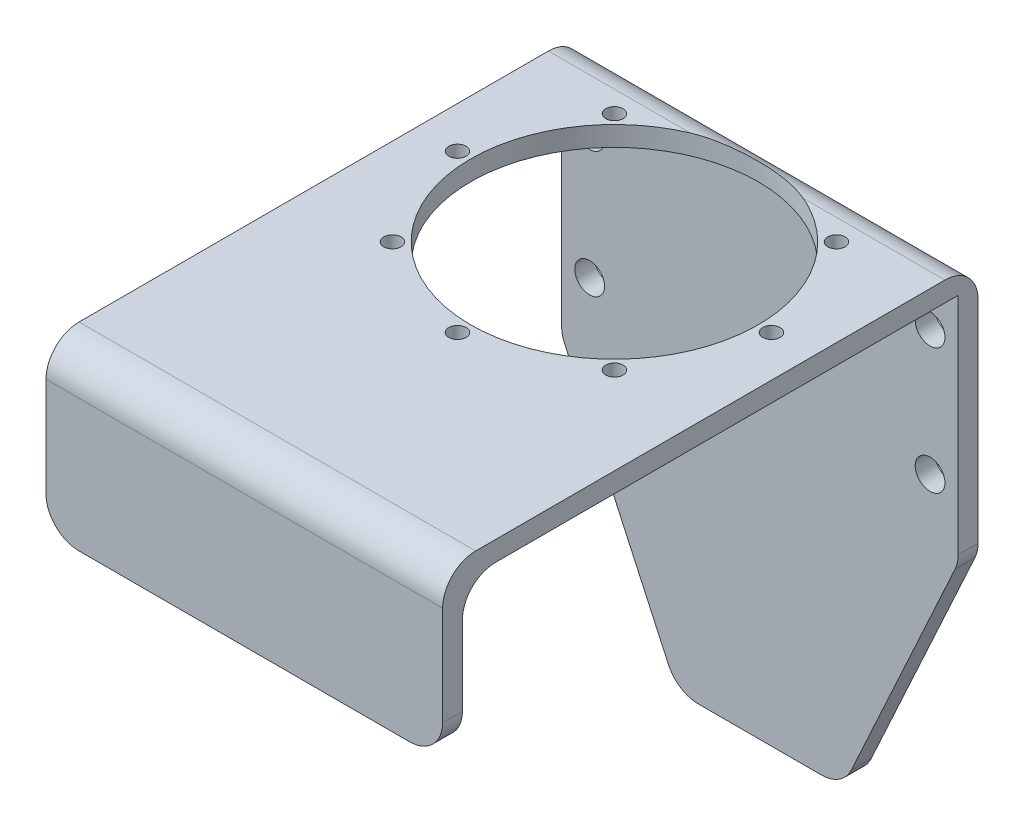
SolidWorks part; units mm, degrees
ref_plane "Alzado" through (0, 0, 0) normal (0, 0, 1) x (1, 0, 0)
ref_plane "Planta" through (0, 0, 0) normal (0, 1, 0) x (1, 0, 0)
ref_plane "Vista lateral" through (0, 0, 0) normal (1, 0, 0) x (0, 0, -1)
sketch "Croquis1" plane through (0, 0, 0) normal (0, 0, 1) x (1, 0, 0)
  line L7 (-92.102, -168.3) -> (-57.102, -244.5)
  line L8 (-92.102, -92.1) -> (27.898, -92.1) construction
  line L9 (-92.102, -92.1) -> (-92.102, -244.5) construction
  line L10 (-92.102, -244.5) -> (27.898, -244.5) construction
  line L11 (27.898, -92.1) -> (27.898, -244.5) construction
  line L12 (27.898, -92.1) -> (27.898, -244.5) construction
  line L13 (-92.102, -92.1) -> (27.898, -92.1) construction
  line L14 (-92.102, -92.1) -> (27.898, -92.1)
  line L15 (-92.102, -92.1) -> (-92.102, -168.3)
  line L17 (27.898, -92.1) -> (27.898, -168.3)
  line L22 (-57.102, -244.5) -> (-7.102, -244.5)
  line L23 (-7.102, -244.5) -> (27.898, -168.3)
  line L24 (-32.102, -168.3) -> (-32.102, -92.1) construction
  line L25 (-92.102, -168.3) -> (27.898, -168.3) construction
  line L26 (-32.102, -130.2) -> (-92.102, -130.2) construction
  line L27 (-62.102, -130.2) -> (-62.102, -92.1) construction
  circle A0 centre (-83.602, -111.15) radius 4.5
  circle A1 centre (-83.602, -149.25) radius 4.5
  circle A2 centre (19.398, -149.25) radius 4.5
  circle A3 centre (19.398, -111.15) radius 4.5
  point P5 (-32.102, -244.5)
  point P16 (-32.102, -244.5)
  point P21 (27.898, -168.3)
  point P24 (-62.102, -111.15)
  point P32 (-88.102, -111.15)
  dimension "D3" = 9
  dimension "D1" = 120
  dimension "D2" = 50
  dimension "D4" = 4
extrude "Saliente-Extruir1" add sketch "Croquis1" along normal blind 6
sketch "Croquis2" plane through (0, 0, 6) normal (0, 0, 1) x (1, 0, 0)
  line L0 (27.898, -168.3) -> (27.898, -92.1) construction
  line L6 (-92.102, -98.1) -> (27.898, -98.1)
  line L7 (-92.102, -98.1) -> (-92.102, -92.1)
  line L8 (-92.102, -92.1) -> (27.898, -92.1)
  line L9 (27.898, -98.1) -> (27.898, -92.1)
  dimension "D1" = 6
extrude "Saliente-Extruir2" add sketch "Croquis2" along normal up to surface (156 mm away)
sketch "Croquis3" plane through (0, 0, 162) normal (0, 0, 1) x (1, 0, 0)
  line L5 (-92.102, -98.1) -> (27.898, -98.1)
  line L6 (-92.102, -98.1) -> (-92.102, -142.1)
  line L7 (-92.102, -142.1) -> (27.898, -142.1)
  line L16 (27.898, -98.1) -> (27.898, -142.1)
  line L17 (27.898, -92.1) -> (-92.102, -92.1) construction
  line L18 (27.898, -168.3) -> (27.898, -98.1) construction
  dimension "50" = 50
extrude "Saliente-Extruir3" add sketch "Croquis3" against normal blind 6
fillet "Redondeo1" radius 10 9 edges at (-32.102, -98.1, 156) (-32.102, -92.1, 0) (-32.102, -92.1, 162) (-92.102, -142.1, 159) (27.898, -142.1, 159) (-92.102, -168.3, 3) (27.898, -168.3, 3) (-7.102, -244.5, 3) (-57.102, -244.5, 3)
sketch "Croquis4" plane through (0, -98.1, 0) normal (0, -1, 0) x (1, 0, 0)
  circle A2 centre (-65.6896, 16.4124) radius 2.621
  circle A3 centre (1.4855, 83.5876) radius 2.621
  circle A4 centre (1.4855, 83.5876) radius 2.621
  circle A5 centre (-65.6896, 16.4124) radius 2.621
  circle A6 centre (15.398, 50) radius 2.621
  circle A7 centre (15.398, 50) radius 2.621
  circle A9 centre (1.4855, 16.4124) radius 2.621
  circle A10 centre (1.4855, 16.4124) radius 2.621
  circle A12 centre (-65.6896, 83.5876) radius 2.621
  circle A13 centre (-65.6896, 83.5876) radius 2.621
  circle A15 centre (-79.602, 50) radius 2.621
  circle A16 centre (-32.102, 97.5) radius 2.621
  circle A17 centre (-32.102, 97.5) radius 2.621
  circle A18 centre (-79.602, 50) radius 2.621
  spline S0 degree 3 poles (-36.0819, 6.6207) (-32.1019, 6.4397) (-28.122, 6.6207) (-24.0966, 7.1778) (-20.0626, 8.1272) (-16.0093, 9.5102) (-12.0574, 11.3088) (-8.2311, 13.545) (-4.6252, 16.1753) (-1.2886, 19.1868) (1.7228, 22.5233) (4.3531, 26.1294) (6.5893, 29.9556) (8.3879, 33.9076) (9.7708, 37.9607) (10.7202, 41.9949) (11.2773, 46.0201) (11.4583, 50.0002) (11.2773, 53.98) (10.7201, 58.0055) (9.7707, 62.0395) (8.3878, 66.0927) (6.5892, 70.0446) (4.353, 73.8709) (1.7226, 77.4768) (-1.2888, 80.8135) (-4.6253, 83.8248) (-8.2314, 86.4552) (-12.0576, 88.6913) (-16.0096, 90.4899) (-20.0627, 91.8728) (-24.0969, 92.8222) (-28.1222, 93.3793) (-32.1022, 93.5603) (-36.0821, 93.3793) (-40.1075, 92.8222) (-44.1415, 91.8727) (-48.1948, 90.4898) (-52.1466, 88.6912) (-55.973, 86.455) (-59.5789, 83.8247) (-62.9155, 80.8132) (-65.9268, 77.4767) (-68.5572, 73.8706) (-70.7934, 70.0444) (-72.592, 66.0924) (-73.9748, 62.0393) (-74.9243, 58.0051) (-75.4813, 53.9799) (-75.6624, 49.9998) (-75.4813, 46.02) (-74.9242, 41.9945) (-73.9748, 37.9605) (-72.5918, 33.9073) (-70.7933, 29.9554) (-68.557, 26.1291) (-65.9267, 22.5232) (-62.9153, 19.1865) (-59.5787, 16.1752) (-55.9727, 13.5448) (-52.1465, 11.3087) (-48.1944, 9.5101) (-44.1414, 8.1272) (-40.1072, 7.1778) (-36.0819, 6.6207) (-32.1019, 6.4397) (-28.122, 6.6207) knots -0.04456 -0.029124 -0.014562 0 0.014563 0.029124 0.044561 0.059997 0.076078 0.092156 0.108579 0.125 0.141423 0.157844 0.173924 0.190003 0.20544 0.220876 0.235439 0.25 0.264563 0.279124 0.294561 0.309997 0.326078 0.342156 0.358579 0.375 0.391423 0.407844 0.423924 0.440003 0.45544 0.470876 0.485439 0.5 0.514563 0.529124 0.544561 0.559997 0.576078 0.592156 0.608579 0.625 0.641423 0.657844 0.673924 0.690003 0.70544 0.720876 0.735439 0.75 0.764563 0.779124 0.794561 0.809997 0.826078 0.842156 0.858579 0.875 0.891423 0.907844 0.923924 0.940003 0.95544 0.970876 0.985438 1 1.014563 1.029124 1.044561 only from (-32.102, 6.5) to (-32.102, 6.5) construction
  spline S1 degree 3 poles (-36.0819, 6.6207) (-32.1019, 6.4397) (-28.122, 6.6207) (-24.0966, 7.1778) (-20.0626, 8.1272) (-16.0093, 9.5102) (-12.0574, 11.3088) (-8.2311, 13.545) (-4.6252, 16.1753) (-1.2886, 19.1868) (1.7228, 22.5233) (4.3531, 26.1294) (6.5893, 29.9556) (8.3879, 33.9076) (9.7708, 37.9607) (10.7202, 41.9949) (11.2773, 46.0201) (11.4583, 50.0002) (11.2773, 53.98) (10.7201, 58.0055) (9.7707, 62.0395) (8.3878, 66.0927) (6.5892, 70.0446) (4.353, 73.8709) (1.7226, 77.4768) (-1.2888, 80.8135) (-4.6253, 83.8248) (-8.2314, 86.4552) (-12.0576, 88.6913) (-16.0096, 90.4899) (-20.0627, 91.8728) (-24.0969, 92.8222) (-28.1222, 93.3793) (-32.1022, 93.5603) (-36.0821, 93.3793) (-40.1075, 92.8222) (-44.1415, 91.8727) (-48.1948, 90.4898) (-52.1466, 88.6912) (-55.973, 86.455) (-59.5789, 83.8247) (-62.9155, 80.8132) (-65.9268, 77.4767) (-68.5572, 73.8706) (-70.7934, 70.0444) (-72.592, 66.0924) (-73.9748, 62.0393) (-74.9243, 58.0051) (-75.4813, 53.9799) (-75.6624, 49.9998) (-75.4813, 46.02) (-74.9242, 41.9945) (-73.9748, 37.9605) (-72.5918, 33.9073) (-70.7933, 29.9554) (-68.557, 26.1291) (-65.9267, 22.5232) (-62.9153, 19.1865) (-59.5787, 16.1752) (-55.9727, 13.5448) (-52.1465, 11.3087) (-48.1944, 9.5101) (-44.1414, 8.1272) (-40.1072, 7.1778) (-36.0819, 6.6207) (-32.1019, 6.4397) (-28.122, 6.6207) knots -0.04456 -0.029124 -0.014562 0 0.014563 0.029124 0.044561 0.059997 0.076078 0.092156 0.108579 0.125 0.141423 0.157844 0.173924 0.190003 0.20544 0.220876 0.235439 0.25 0.264563 0.279124 0.294561 0.309997 0.326078 0.342156 0.358579 0.375 0.391423 0.407844 0.423924 0.440003 0.45544 0.470876 0.485439 0.5 0.514563 0.529124 0.544561 0.559997 0.576078 0.592156 0.608579 0.625 0.641423 0.657844 0.673924 0.690003 0.70544 0.720876 0.735439 0.75 0.764563 0.779124 0.794561 0.809997 0.826078 0.842156 0.858579 0.875 0.891423 0.907844 0.923924 0.940003 0.95544 0.970876 0.985438 1 1.014563 1.029124 1.044561 only from (-32.102, 6.5) to (-32.102, 6.5)
  dimension "D1" = 1
  dimension "D2" = 1
  dimension "D3" = 1
  dimension "D4" = 1
  dimension "D5" = 1
  dimension "D6" = 1
  dimension "D7" = 1
extrude "Cortar-Extruir1" cut sketch "Croquis4" against normal through all
